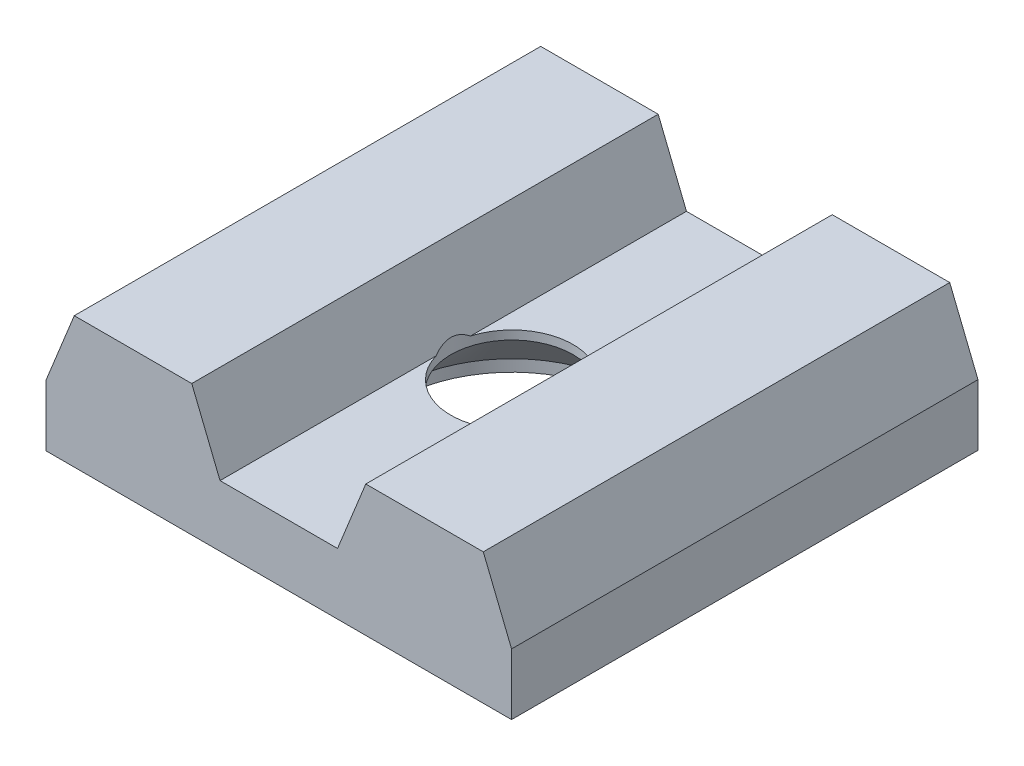
SolidWorks part; units mm, degrees
material "ABS"
ref_plane "正面" through (0, 0, 0) normal (0, 0, 1) x (1, 0, 0)
ref_plane "平面" through (0, 0, 0) normal (0, 1, 0) x (1, 0, 0)
ref_plane "右側面" through (0, 0, 0) normal (1, 0, 0) x (0, 0, -1)
sketch "ｽｹｯﾁ1" plane through (0, 0, 0) normal (0, 0, 1) x (1, 0, 0)
  line L0 (-3.5076, 0) -> (-1.4924, 0)
  line L1 (-1.4924, 0) -> (-1.0076, -1.2)
  line L2 (-1.0076, -1.2) -> (1.0076, -1.2)
  line L3 (0, 0) -> (0, -4.2434) construction
  line L4 (1.4924, 0) -> (1.0076, -1.2)
  line L5 (3.5076, 0) -> (1.4924, 0)
  line L6 (-2.5, 1.2) -> (-2.5, -0.4451) construction
  line L7 (2.5, 1.2) -> (2.5, -0.4451) construction
  line L8 (-3.5076, 0) -> (-3.9924, -1.2)
  line L9 (3.5076, 0) -> (3.9924, -1.2)
  line L17 (-1, -1.2) -> (-2, -2.2) construction
  line L18 (-2, -2.2) -> (-2, -2.5) construction
  line L19 (-2, -2.5) -> (2, -2.5) construction
  line L20 (-3.9924, -1.2) -> (-3.9924, -2.5)
  line L21 (2, -2.2) -> (2, -2.5) construction
  line L22 (1, -1.2) -> (2, -2.2) construction
  line L23 (-3.9924, -2.5) -> (3.9924, -2.5)
  line L24 (3.9924, -2.5) -> (3.9924, -1.2)
  point P8 (0, -1.2)
  point P16 (-2.5, 0)
  point P18 (2.5, 0)
  dimension "D1" = 1.2
  dimension "D2" = 5
  dimension "D3" = 22
  dimension "D4" = 2
  dimension "D5" = 4
  dimension "D6" = 1.3
extrude "ﾎﾞｽ - 押し出し1" add sketch "ｽｹｯﾁ1" along normal blind 8
sketch "ｽｹｯﾁ2" plane through (0, -2.5, 0) normal (0, -1, 0) x (1, 0, 0)
  line L0 (0, 0) -> (0, 8) construction
  line L1 (-3.9924, 8) -> (3.9924, 8) construction
  circle A0 centre (0, 4) radius 1.05
  dimension "D1" = 2.1
extrude "ｶｯﾄ - 押し出し1" cut sketch "ｽｹｯﾁ2" against normal through all
sketch "ｽｹｯﾁ4" plane through (0, 0, 0) normal (1, 0, 0) x (0, 0, -1)
  line L0 (-4, -2.5) -> (-4, 0) construction
  line L1 (-8, -2.5) -> (0, -2.5) construction
  line L2 (-8, 0) -> (0, 0) construction
  line L3 (-4, -2.5) -> (-2, -2.5)
  line L4 (-2, -2.5) -> (-2, -2.3)
  line L5 (-2, -2.3) -> (-3, -1.3)
  line L6 (-3, -1.3) -> (-4, -1.3)
  line L7 (-4, -1.3) -> (-4, -2.5)
  dimension "D1" = 2
  dimension "D2" = 2
  dimension "D3" = 1.2
  dimension "D4" = 135
revolve "ｶｯﾄ - 回転1" cut sketch "ｽｹｯﾁ4" angle 360 about L0
chamfer "面取り1" distance 0.25 angle 45 4 edges at (3.9924, -2.5, 4) (0, -2.5, 8) (-3.9924, -2.5, 4) (0, -2.5, 0)
